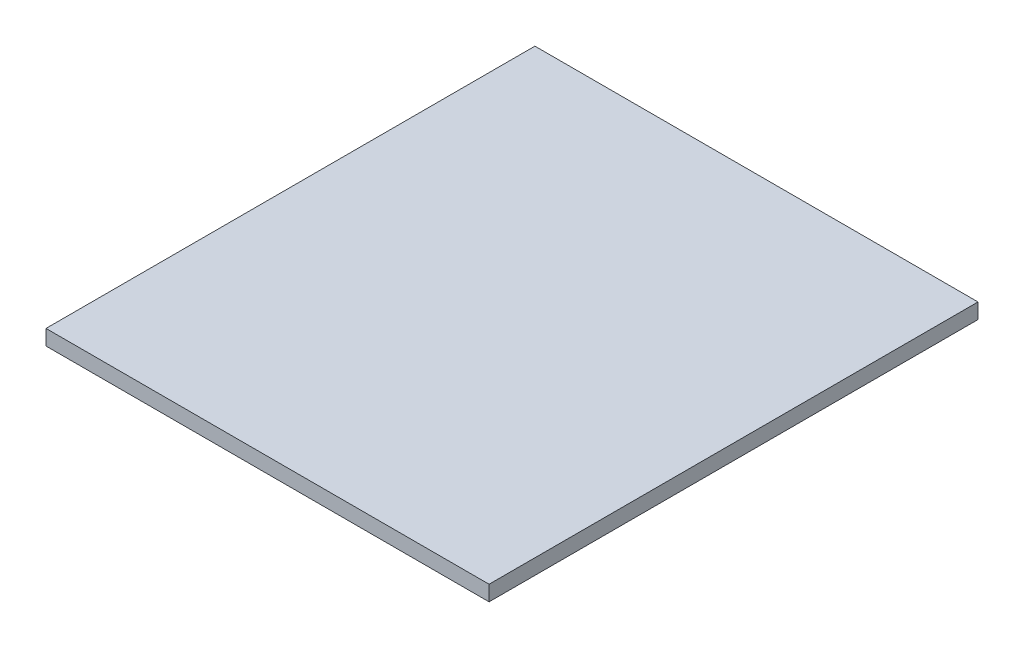
SolidWorks part; units mm, degrees
ref_plane "Front Plane" through (0, 0, 0) normal (0, 0, 1) x (1, 0, 0)
ref_plane "Top Plane" through (0, 0, 0) normal (0, 1, 0) x (1, 0, 0)
ref_plane "Right Plane" through (0, 0, 0) normal (1, 0, 0) x (0, 0, -1)
other "Configuration Table"
sketch "Sketch1" plane through (0, 0, 0) normal (0, 0, 1) x (1, 0, 0)
  line L1 (40, 1300) -> (330, 1300)
  line L2 (40, 1300) -> (40, 1310)
  line L3 (40, 1310) -> (330, 1310)
  line L4 (330, 1300) -> (330, 1310)
extrude "PRESS_kova_tabani_1" add sketch "Sketch1" against normal blind 320 from offset 140 separate body
